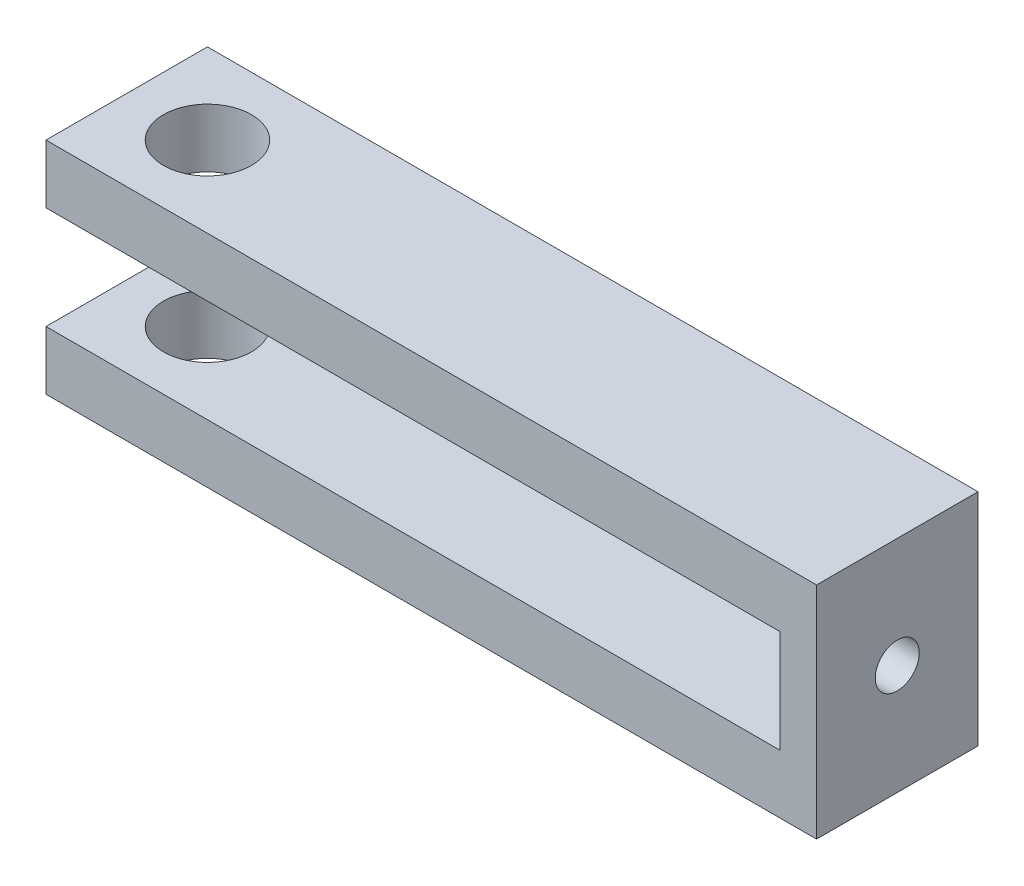
SolidWorks part; units mm, degrees
ref_plane "正面" through (0, 0, 0) normal (0, 0, 1) x (1, 0, 0)
ref_plane "平面" through (0, 0, 0) normal (0, 1, 0) x (1, 0, 0)
ref_plane "右側面" through (0, 0, 0) normal (1, 0, 0) x (0, 0, -1)
sketch "ｽｹｯﾁ1" plane through (0, 0, 0) normal (0, 0, 1) x (1, 0, 0)
  line L0 (-105, 15) -> (-105, 7)
  line L1 (-105, 7) -> (-5, 7)
  line L2 (-5, 7) -> (-5, -7)
  line L3 (-5, -7) -> (-105, -7)
  line L4 (-105, -7) -> (-105, -15)
  line L5 (-105, -15) -> (0, -15)
  line L6 (0, -15) -> (0, 15)
  line L7 (0, 15) -> (-105, 15)
  line L8 (55, 0) -> (-55, 0) construction
  line L10 (0, -55) -> (0, 55) construction
  dimension "D1" = 7
  dimension "D2" = 7
  dimension "D3" = 8
  dimension "D4" = 8
  dimension "D5" = 105
  dimension "D6" = 100
  dimension "D7" = 100
  dimension "D8" = 0
extrude "ﾎﾞｽ - 押し出し1" add sketch "ｽｹｯﾁ1" along normal blind 22
sketch "ｽｹｯﾁ2" plane through (0, -15, 0) normal (0, -1, 0) x (1, 0, 0)
  line L0 (-105, 22) -> (-105, 0) construction
  line L1 (-105, 22) -> (0, 22) construction
  circle A0 centre (-94, 11) radius 6
  dimension "D1" = 12
  dimension "D2" = 11
  dimension "D3" = 11
extrude "ｶｯﾄ - 押し出し1" cut sketch "ｽｹｯﾁ2" against normal through all
sketch "ｽｹｯﾁ3" plane through (0, 0, 0) normal (1, 0, 0) x (0, 0, -1)
  line L0 (55, 0) -> (-55, 0) construction
  line L1 (0, 55) -> (0, -55) construction
  circle A0 centre (-11, 0) radius 3
  dimension "D1" = 6
  dimension "D2" = 11
extrude "ｶｯﾄ - 押し出し2" cut sketch "ｽｹｯﾁ3" against normal through all
